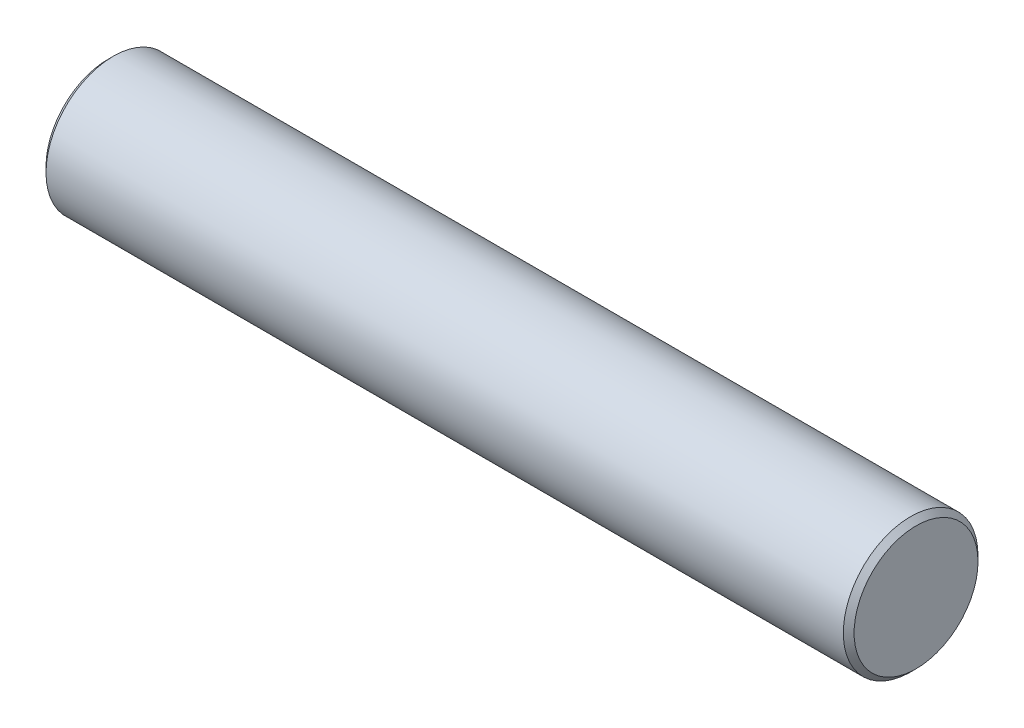
SolidWorks part; units mm, degrees
ref_plane "Front Plane" through (0, 0, 0) normal (0, 0, 1) x (1, 0, 0)
ref_plane "Top Plane" through (0, 0, 0) normal (0, 1, 0) x (1, 0, 0)
ref_plane "Right Plane" through (0, 0, 0) normal (1, 0, 0) x (0, 0, -1)
sketch "Sketch1" plane through (0, 0, 0) normal (0, 0, 1) x (1, 0, 0)
  line L1 (0, 0) -> (-30, 0)
  line L2 (0, 0) -> (0, 2.5)
  line L3 (0, 2.5) -> (-30, 2.5)
  line L4 (-30, 0) -> (-30, 2.5)
  dimension "D1" = 30
  dimension "D2" = 2.5
revolve "Revolve1" add sketch "Sketch1" angle 360 about L1
chamfer "Chamfer1" distance 0.2 angle 45 2 edges at (0, 0, -2.5) (-30, 0, -2.5)
ref_plane "Plane1" through (-15, 0, 0) normal (-1, 0, 0) x (0, 0, 1)
ref_plane "Plane2" through (-15, 0, 0) normal (1, 0, 0) x (0, 0, -1)
